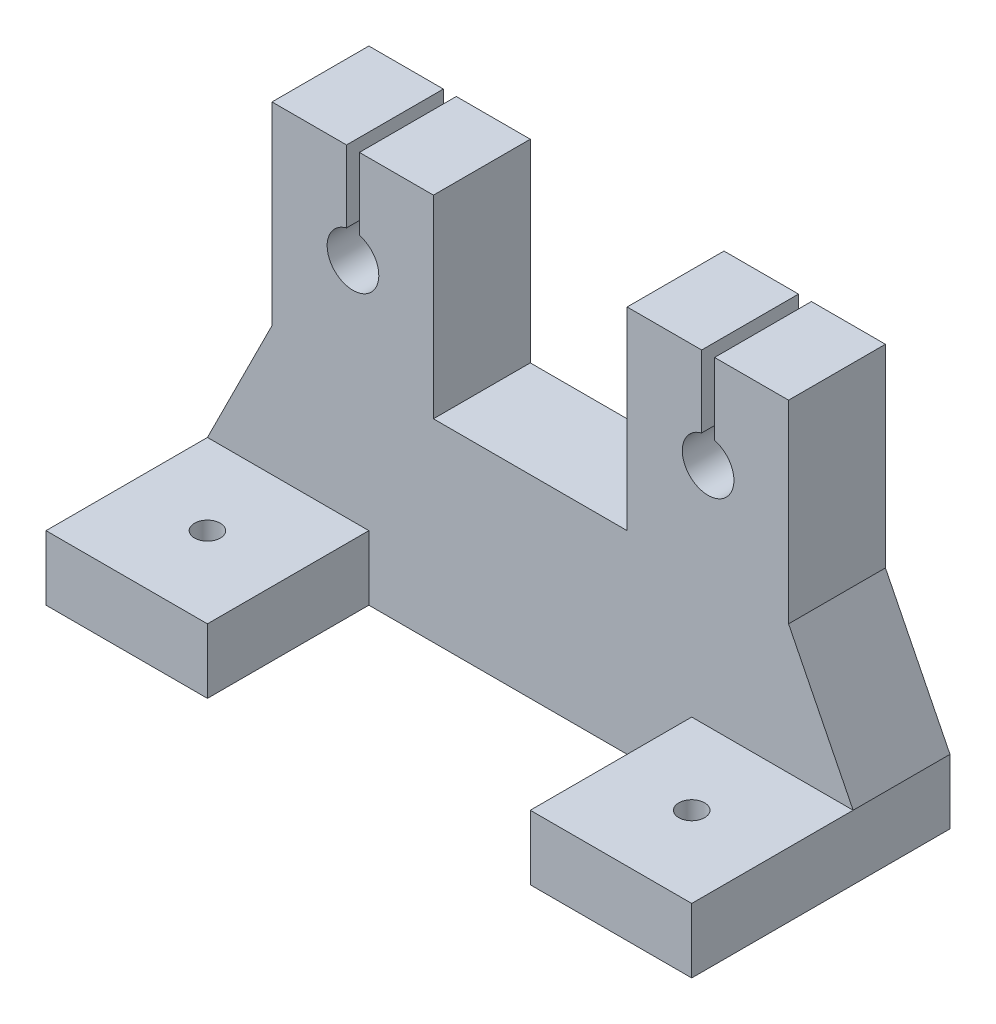
SolidWorks part; units mm, degrees
ref_plane "Front Plane" through (0, 0, 0) normal (0, 0, 1) x (1, 0, 0)
ref_plane "Top Plane" through (0, 0, 0) normal (0, 1, 0) x (1, 0, 0)
ref_plane "Right Plane" through (0, 0, 0) normal (1, 0, 0) x (0, 0, -1)
sketch "Sketch1" plane through (0, 0, 0) normal (0, 0, 1) x (1, 0, 0)
  line L1 (-15, 0) -> (0, 0)
  line L5 (-40, 30) -> (-28.46, 30)
  line L6 (15, 30) -> (26.54, 30)
  line L8 (50, -30) -> (0, -30)
  line L9 (50, -20) -> (50, -30)
  line L10 (0, -30) -> (-50, -30)
  line L11 (-50, -30) -> (-50, -20)
  line L12 (-15, 0) -> (-15, 30)
  line L13 (15, 0) -> (15, 30)
  line L14 (-40, 0) -> (-40, 30)
  line L15 (40, 0) -> (40, 30)
  line L16 (-50, -20) -> (-40, 0)
  line L17 (40, 0) -> (50, -20)
  line L18 (-28.46, 30) -> (-28.46, 18.873)
  line L19 (-26.46, 30) -> (-26.46, 18.873)
  line L20 (-26.46, 30) -> (-15, 30)
  line L21 (28.54, 30) -> (40, 30)
  line L22 (26.54, 30) -> (26.54, 18.873)
  line L23 (28.54, 30) -> (28.54, 18.873)
  line L24 (0, 0) -> (15, 0)
  arc A5 (-28.46, 18.873) -> (-26.46, 18.873) centre (-27.46, 15) ccw
  arc A6 (26.54, 18.873) -> (28.54, 18.873) centre (27.54, 15) ccw
  dimension "D4" = 40
  dimension "D10" = 10
  dimension "D1" = 30
  dimension "D2" = 30
  dimension "D3" = 15
  dimension "D5" = 40
  dimension "D6" = 15
  dimension "D7" = 15
  dimension "D8" = 50
  dimension "D9" = 50
  dimension "D11" = 10
  dimension "D12" = 55
extrude "Boss-Extrude1" add sketch "Sketch1" against normal blind 15
ref_plane "Plane1" through (0, 0, 0) normal (0, 0, 1) x (1, 0, 0)
sketch "Sketch2" plane through (0, 0, 0) normal (0, 0, 1) x (1, 0, 0)
  line L0 (-50, -20) -> (-25, -20)
  line L1 (-25, -20) -> (-25, -30)
  line L2 (-50, -30) -> (50, -30) construction
  line L3 (50, -20) -> (25, -20)
  line L4 (25, -30) -> (50, -30)
  line L5 (-50, -20) -> (-50, -30)
  line L6 (-50, -30) -> (-25, -30)
  line L7 (25, -20) -> (25, -30)
  line L8 (50, -30) -> (50, -20)
  dimension "D1" = 25
  dimension "D2" = 25
extrude "Boss-Extrude2" add sketch "Sketch2" along normal blind 25
ref_plane "Plane2" through (0, -20, 0) normal (0, 1, 0) x (1, 0, 0)
sketch "Sketch3" plane through (0, -20, 0) normal (0, 1, 0) x (1, 0, 0)
  circle A0 centre (-37.5, -12.5) radius 2
  circle A1 centre (37.5, -12.5) radius 2
extrude "Cut-Extrude1" cut sketch "Sketch3" against normal blind 10
